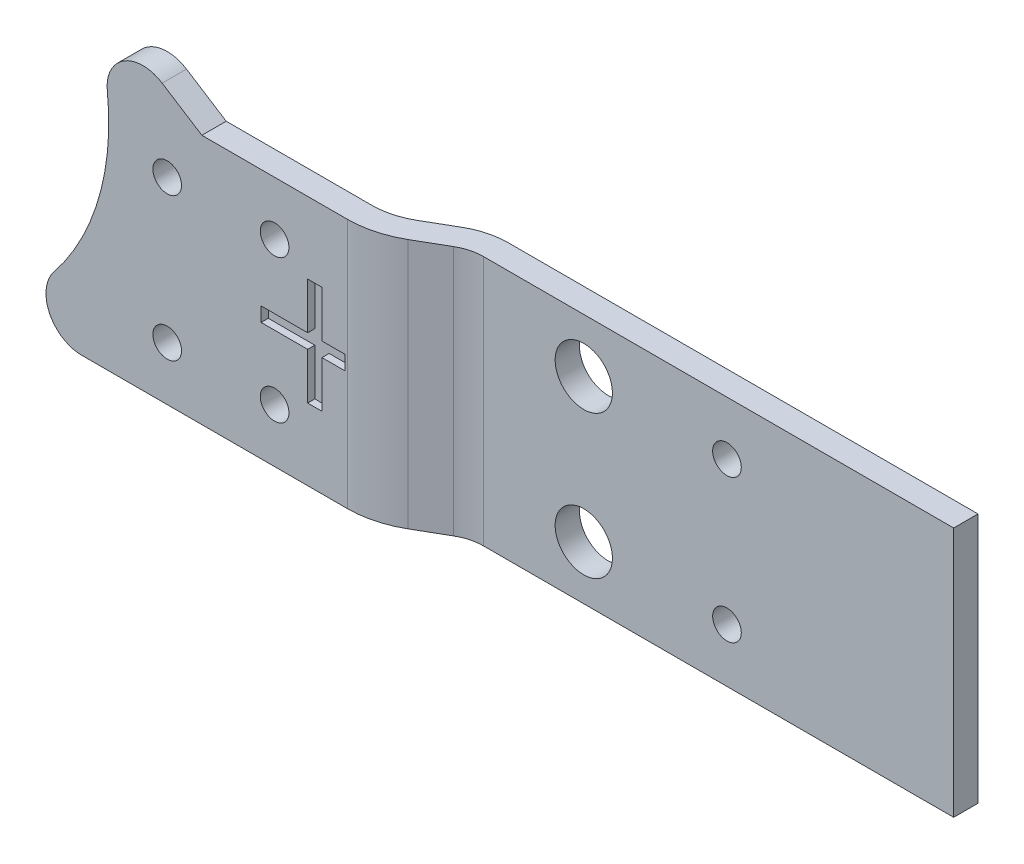
SolidWorks part; units mm, degrees
ref_plane "前视基准面" through (0, 0, 0) normal (0, 0, 1) x (1, 0, 0)
ref_plane "上视基准面" through (0, 0, 0) normal (0, 1, 0) x (1, 0, 0)
ref_plane "右视基准面" through (0, 0, 0) normal (1, 0, 0) x (0, 0, -1)
sketch "Sketch1" plane through (0, 0, 0) normal (0, 0, 1) x (1, 0, 0)
  line L0 (0, -30) -> (80, -30)
  line L1 (80, -30) -> (80, 5)
  line L2 (80, 5) -> (48, 5)
  line L4 (48, 5) -> (16.1141, 25.3049)
  arc A0 (16.1141, 25.3049) -> (0, -30) centre (0, 0) ccw
  dimension "D1" = 80
  dimension "D2" = 60
  dimension "D3" = 35
  dimension "D4" = 32
extrude "Boss-Extrude1" add sketch "Sketch1" along normal blind 3.4
sketch "Sketch2" plane through (0, 0, 3.4) normal (0, 0, 1) x (1, 0, 0)
  circle A0 centre (48, -12.5) radius 2.75
  circle A3 centre (48, -12.5) radius 2
  dimension "D2" = 5.5
sketch "Sketch3" plane through (0, 0, 3.4) normal (0, 0, 1) x (1, 0, 0)
  circle A0 centre (0, 0) radius 5
  dimension "D1" = 10
extrude "Cut-Extrude1" cut sketch "Sketch3" against normal blind 6
sketch "Sketch5" plane through (0, 0, 3.4) normal (0, 0, 1) x (1, 0, 0)
  line L0 (0, 20) -> (0, 0) construction
  line L1 (0, 0) -> (-18.1865, -10.5) construction
  arc A0 (0, 10) -> (-8.6603, -5) centre (0, 0) ccw
  arc A2 (0, 18) -> (-15.5885, -9) centre (0, 0) ccw
  arc A3 (-8.6603, -5) -> (-15.5885, -9) centre (-12.1244, -7) cw
  arc A4 (0, 18) -> (0, 10) centre (0, 14) cw
  point P4 (0, 18)
  point P6 (0, 10)
  point P8 (-8.6603, -5)
  point P9 (-15.5885, -9)
  dimension "D1" = 120
  dimension "D2" = 21
extrude "Cut-Extrude2" cut sketch "Sketch5" against normal blind 10
sketch "Sketch6" plane through (0, 0, 0) normal (0, 0, -1) x (-1, 0, 0)
  circle A0 centre (0, 0) radius 35
extrude "Cut-Extrude3" cut sketch "Sketch6" against normal blind 10
sketch "Sketch7" plane through (0, 0, 3.4) normal (0, 0, 1) x (1, 0, 0)
  line L0 (62.7754, -13.5) -> (62.7754, -20)
  line L1 (64.7754, -5) -> (62.7754, -5)
  line L2 (64.7754, -5) -> (64.7754, -11.5)
  line L3 (64.7754, -20) -> (62.7754, -20)
  line L4 (62.7754, -5) -> (62.7754, -11.5)
  line L5 (80, 5) -> (48, 5) construction
  line L7 (80, -30) -> (80, 5) construction
  line L8 (62.7754, -11.5) -> (56.2754, -11.5)
  line L9 (71.2754, -11.5) -> (64.7754, -11.5)
  line L10 (71.2754, -11.5) -> (71.2754, -13.5)
  line L11 (71.2754, -13.5) -> (64.7754, -13.5)
  line L12 (56.2754, -11.5) -> (56.2754, -13.5)
  line L17 (62.7754, -13.5) -> (56.2754, -13.5)
  line L18 (63.9087, -13.5) -> (63.642, -13.5)
  line L19 (64.7754, -13.5) -> (64.7754, -20)
  point P0 (63.9087, -12.5)
  point P9 (80, -12.5)
  point P10 (63.7754, -13.5)
  dimension "D1" = 15
  dimension "D2" = 2
  dimension "D3" = 0
  dimension "D4" = 2
  dimension "D5" = 15
  dimension "D6" = 16.5
extrude "Cut-Extrude4" cut sketch "Sketch7" against normal blind 1
sketch "Sketch8" plane through (0, 0, 0) normal (0, 0, -1) x (-1, 0, 0)
  line L0 (-80, 5) -> (-48, 5) construction
  line L1 (-80, -30) -> (-68, -30)
  line L2 (-80, -30) -> (-80, 5)
  line L3 (-80, 5) -> (-68, 5)
  line L4 (-68, -30) -> (-68, 5)
  dimension "D1" = 20
extrude "Cut-Extrude5" cut sketch "Sketch8" against normal up to next
sketch "Sketch9" plane through (0, 5, 0) normal (0, 1, 0) x (1, 0, 0)
  line L0 (68, 0) -> (68.3205, 0)
  line L1 (83, 5) -> (148, 5)
  line L2 (73.3205, 1.3397) -> (77.3397, 3.6603)
  line L3 (68, -3.4) -> (68.3205, -3.4)
  line L4 (75.0205, -1.6047) -> (79.0397, 0.7158)
  line L5 (82.3397, 5) -> (83, 5)
  line L6 (68, 0) -> (48, 0) construction
  line L7 (82.3397, 1.6) -> (83, 1.6)
  line L8 (83, 1.6) -> (148, 1.6)
  line L9 (68, 0) -> (68, -3.4)
  line L10 (148, 1.6) -> (148, 5)
  arc A0 (77.3397, 3.6603) -> (82.3397, 5) centre (82.3397, -5) cw
  arc A1 (68.3205, 0) -> (73.3205, 1.3397) centre (68.3205, 10) ccw
  arc A2 (68.3205, -3.4) -> (75.0205, -1.6047) centre (68.3205, 10) ccw
  arc A3 (79.0397, 0.7158) -> (82.3397, 1.6) centre (82.3397, -5) cw
  point P11 (68, 0)
  dimension "D1" = 15
  dimension "D4" = 10
  dimension "D2" = 5
  dimension "D3" = 150
  dimension "D6" = 65
  dimension "D5" = 3.4
extrude "Boss-Extrude2" add sketch "Sketch9" against normal up to surface (35 mm away) up to face at (43.0139, -30, 1.7)
sketch "Sketch10" plane through (0, 0, -5) normal (0, 0, -1) x (-1, 0, 0)
  line L0 (-96.3397, 5) -> (-96.3397, -30) construction
  line L1 (-148, 5) -> (-82.3397, 5) construction
  line L2 (-82.3397, -30) -> (-148, -30) construction
  line L3 (-82.3397, -30) -> (-82.3397, 5) construction
  line L4 (-82.3397, -12.5) -> (-106.6658, -12.5) construction
  circle A0 centre (-96.3397, -2.5) radius 4
  circle A1 centre (-96.3397, -22.5) radius 4
  dimension "D2" = 10
  dimension "D1" = 14
extrude "Cut-Extrude6" cut sketch "Sketch10" against normal blind 10
sketch "Sketch11" plane through (0, 0, 0) normal (0, 0, -1) x (-1, 0, 0)
  line L0 (-68.3205, -30) -> (-68.3205, 5) construction
  circle A0 centre (-58.1603, -22.5) radius 2
  circle A1 centre (-58.1603, -2.5) radius 2
  circle A4 centre (-43.1603, -22.5) radius 2
  circle A5 centre (-43.1603, -2.5) radius 2
  point P6 (-68.3205, -12.5)
  dimension "D1" = 4
  dimension "D4" = 15
  dimension "D5" = 15
  dimension "D2" = 10
  dimension "D3" = 10
extrude "Cut-Extrude7" cut sketch "Sketch11" against normal up to next
sketch "Sketch12" plane through (0, 0, -5) normal (0, 0, -1) x (-1, 0, 0)
  line L0 (-60.1603, -22.5) -> (-138.46, -22.5) construction
  line L1 (-58.1603, -2.5) -> (-138.46, -2.5) construction
  circle A0 centre (-116.3397, -22.5) radius 2
  circle A1 centre (-116.3397, -2.5) radius 2
  circle A2 centre (-58.1603, -22.5) radius 2 construction
  circle A3 centre (-96.3397, -22.5) radius 4 construction
  circle A4 centre (-96.3397, -2.5) radius 4 construction
  dimension "D1" = 20
  dimension "D2" = 20
extrude "Cut-Extrude8" cut sketch "Sketch12" against normal up to next
fillet "Fillet1" radius 5 2 edges at (31.3204, 15.6215, 1.7) (18.0278, -30, 1.7)
